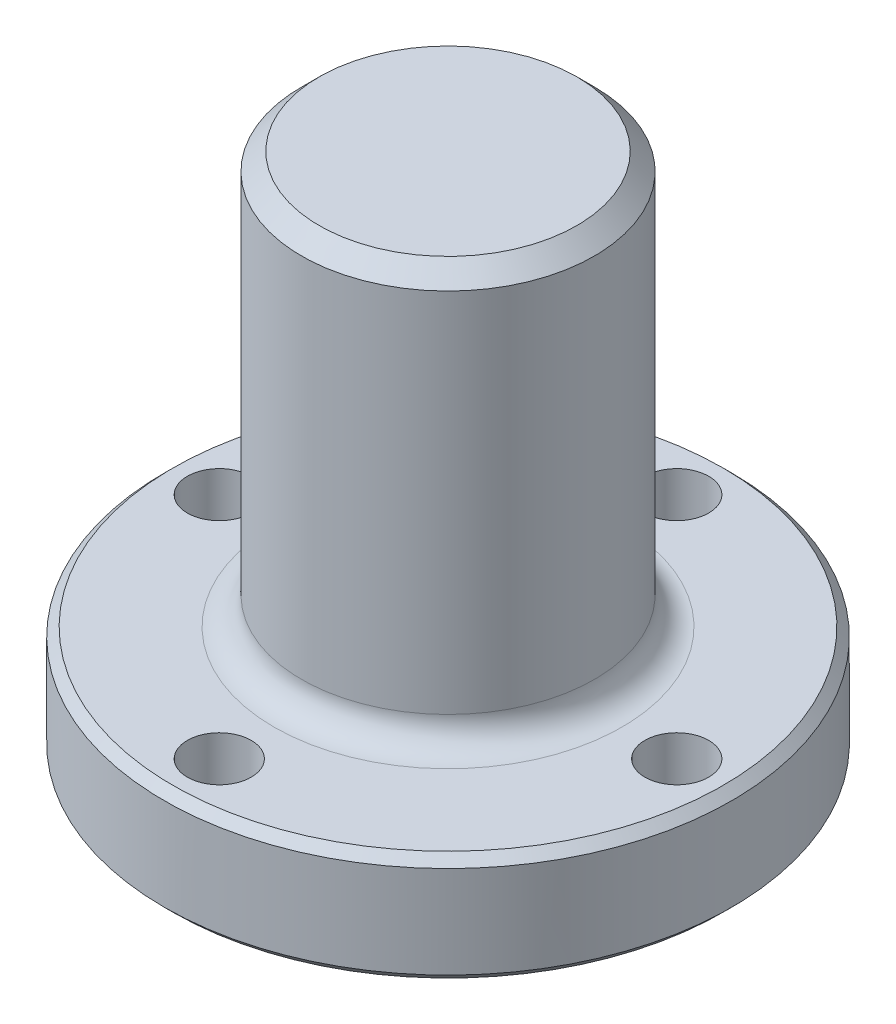
SolidWorks part; units mm, degrees
ref_plane "Front Plane" through (0, 0, 0) normal (1, 0, 0) x (0, 1, 0)
ref_plane "Top Plane" through (0, 0, 0) normal (0, 0, 1) x (0, 1, 0)
ref_plane "Right Plane" through (0, 0, 0) normal (0, 1, 0) x (-1, 0, 0)
sketch "Sketch1" plane through (0, 0, 0) normal (0, 0, 1) x (0, 1, 0)
  line L0 (-25.0317, 0) -> (-25.0317, 8.7122)
  line L1 (-25.0317, 8.7122) -> (-20.2057, 8.7122)
  line L2 (-20.2057, 8.7122) -> (-20.2057, 24.6126)
  line L3 (-20.2057, 24.6126) -> (-10.6807, 24.6126)
  line L4 (-10.6807, 24.6126) -> (-10.6807, 12.7)
  line L5 (-10.6807, 12.7) -> (25.0317, 12.7)
  line L6 (25.0317, 12.7) -> (25.0317, 0)
  line L7 (25.0317, 0) -> (-25.0317, 0)
  line L8 (-50.4317, 0) -> (50.4317, 0) construction
  point P10 (0, 0)
  dimension "D1" = 35.7124
  dimension "D2" = 45.2374
  dimension "D3" = 50.0634
  dimension "D4" = 11.9126
  dimension "D5" = 15.9004
  dimension "D6" = 24.6126
revolve "Revolve1" add sketch "Sketch1" angle 360 about L8
fillet "Fillet1" radius 2.3876 1 edges at (0, -10.6807, -12.7)
chamfer "Chamfer1" distance 0.762 angle 45 3 edges at (0, -10.6807, -24.6126) (0, -20.2057, -24.6126) (0, -25.0317, -8.7122)
chamfer "Chamfer2" distance 1.524 angle 45 1 edges at (0, 25.0317, -12.7)
sketch "Sketch2" plane through (0, 0, 0) normal (0, 1, 0) x (-1, 0, 0)
  circle A0 centre (19.8374, 0) radius 2.7686
  circle A1 centre (0, 19.8374) radius 2.7686
  circle A2 centre (-19.8374, 0) radius 2.7686
  circle A3 centre (0, -19.8374) radius 2.7686
  point P8 (0, 0)
  dimension "D1" = 5.5372
  dimension "D2" = 5.5372
  dimension "D3" = 5.5372
  dimension "D4" = 5.5372
  dimension "D5" = 19.8374
  dimension "D6" = 19.8374
  dimension "D7" = 39.6748
  dimension "D8" = 19.8374
  dimension "D9" = 19.8374
  dimension "D10" = 39.6748
extrude "Cut-Extrude2" cut sketch "Sketch2" against normal blind 10.6807 from offset 10.6807
